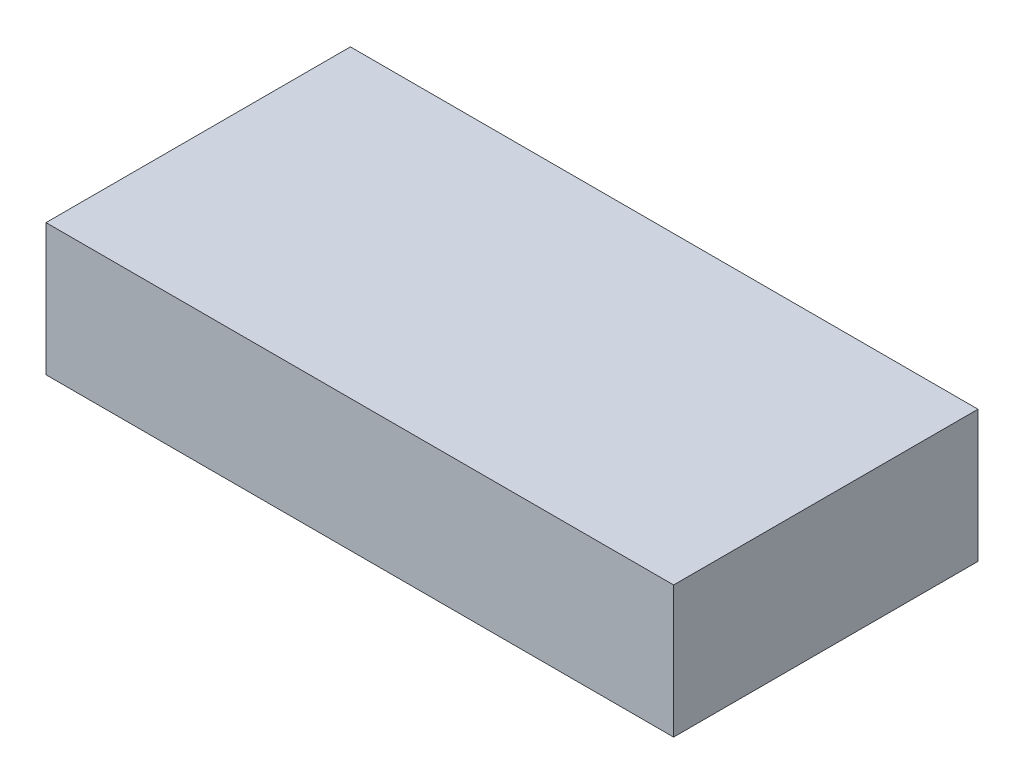
SolidWorks part; units mm, degrees
ref_plane "Front Plane" through (0, 0, 0) normal (0, 0, 1) x (1, 0, 0)
ref_plane "Top Plane" through (0, 0, 0) normal (0, 1, 0) x (1, 0, 0)
ref_plane "Right Plane" through (0, 0, 0) normal (1, 0, 0) x (0, 0, -1)
sketch "Sketch1" plane through (0, 0, 0) normal (0, 1, 0) x (1, 0, 0)
  line L1 (-100, 48.5) -> (100, 48.5)
  line L2 (-100, 48.5) -> (-100, -48.5)
  line L3 (-100, -48.5) -> (100, -48.5)
  line L4 (100, 48.5) -> (100, -48.5)
  line L5 (-100, 48.5) -> (100, -48.5) construction
  line L6 (-100, -48.5) -> (100, 48.5) construction
  point P0 (0, 0)
  dimension "D1" = 200
  dimension "D2" = 97
extrude "Boss-Extrude1" add sketch "Sketch1" along normal blind 42
